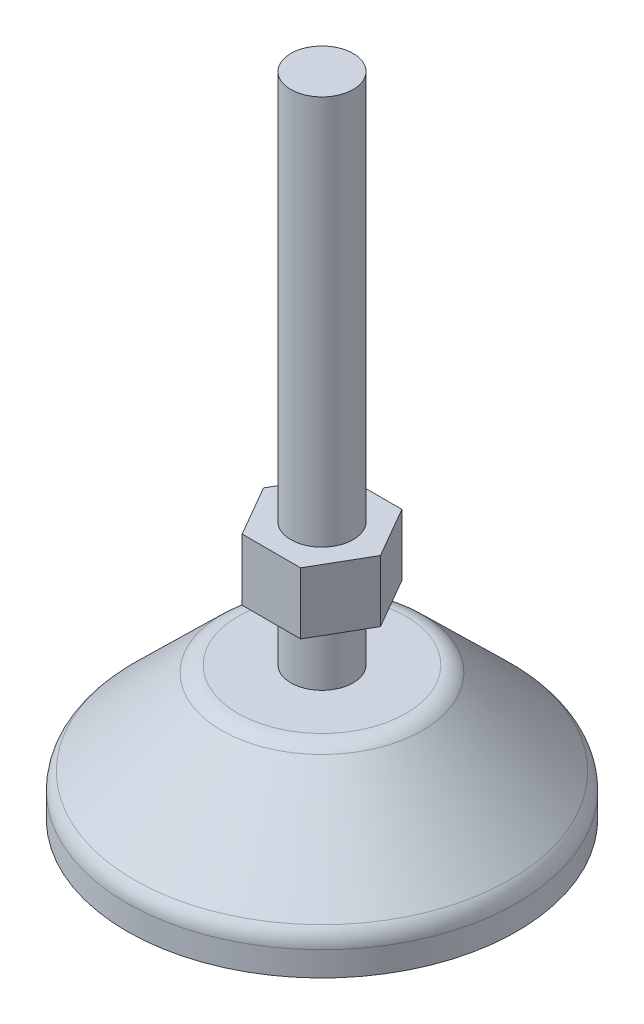
SolidWorks part; units mm, degrees
ref_plane "前视基准面" through (0, 0, 0) normal (0, 0, 1) x (1, 0, 0)
ref_plane "上视基准面" through (0, 0, 0) normal (0, 1, 0) x (1, 0, 0)
ref_plane "右视基准面" through (0, 0, 0) normal (1, 0, 0) x (0, 0, -1)
sketch "草图1" plane through (0, 0, 0) normal (0, 0, 1) x (1, 0, 0)
  line B0 (0, 0) -> (25, 0)
  line B1 (4, 33) -> (7.5, 33)
  line B2 (0, 83) -> (0, 0)
  line B3 (4, 33) -> (4, 83)
  line B4 (7.5, 33) -> (7.5, 25.1)
  line B5 (4, 25.1) -> (7.5, 25.1)
  line B6 (4, 25.1) -> (4, 17.1)
  line B7 (25, 0) -> (25, 3.1347)
  line B8 (24.0966, 5.2804) -> (12.8743, 16.2457)
  line B9 (10.7777, 17.1) -> (4, 17.1)
  line B10 (4, 83) -> (0, 83)
  arc B11 (25, 3.1347) -> (24.0966, 5.2804) centre (22, 3.1347) ccw
  arc B12 (12.8743, 16.2457) -> (10.7777, 17.1) centre (10.7777, 14.1) ccw
sketch_block_instance "A$C10284B12-1"
sketch_block "A$C10284B12"
revolve "旋转1" add sketch "草图1" angle 360 about L2
sketch "草图3" plane through (0, 33, 0) normal (0, 1, 0) x (1, 0, 0)
  line L1 (7.5, 0) -> (3.75, 6.4952)
  line L2 (3.75, 6.4952) -> (-3.75, 6.4952)
  line L3 (-3.75, 6.4952) -> (-7.5, 0)
  line L4 (-7.5, 0) -> (-3.75, -6.4952)
  line L5 (-3.75, -6.4952) -> (3.75, -6.4952)
  line L6 (3.75, -6.4952) -> (7.5, 0)
  circle A1 centre (0, 0) radius 11.7684
extrude "切除-拉伸1" cut sketch "草图3" against normal blind 10
